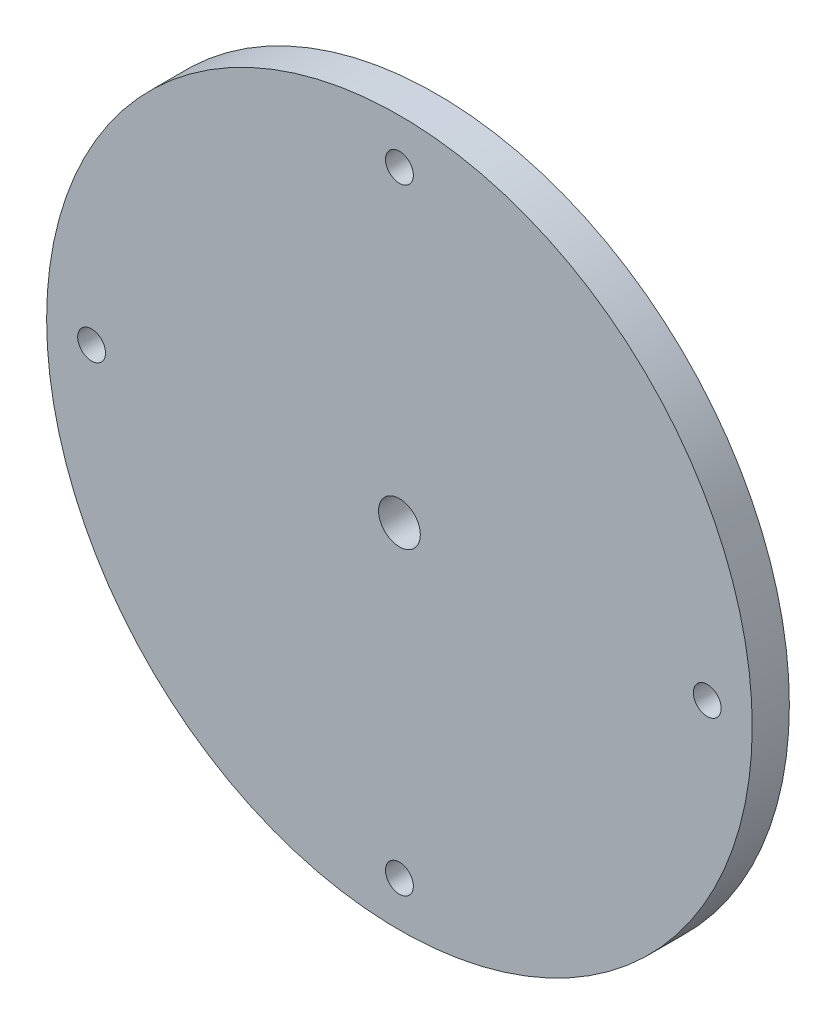
SolidWorks part; units mm, degrees
ref_plane "Front Plane" through (0, 0, 0) normal (0, 0, 1) x (1, 0, 0)
ref_plane "Top Plane" through (0, 0, 0) normal (0, 1, 0) x (1, 0, 0)
ref_plane "Right Plane" through (0, 0, 0) normal (1, 0, 0) x (0, 0, -1)
sketch "Sketch2" plane through (0, 0, 0) normal (0, 0, 1) x (1, 0, 0)
  line L0 (-76, 0) -> (76, 0) construction
  line L2 (0, -76) -> (0, 76) construction
  circle A0 centre (0, 0) radius 76
  circle A1 centre (0, 66.31) radius 3
  circle A2 centre (0, -66.31) radius 3
  circle A3 centre (66.31, 0) radius 3
  circle A4 centre (-66.31, 0) radius 3
  circle A5 centre (0, 0) radius 4.5
  dimension "D1" = 152
  dimension "D6" = 6
  dimension "D7" = 6
  dimension "D8" = 6
  dimension "D9" = 6
  dimension "9.525" = 9
  dimension "D2" = 9.69
  dimension "D3" = 9.69
  dimension "D4" = 9.69
  dimension "D5" = 9.69
extrude "Boss-Extrude1" add sketch "Sketch2" along normal blind 8 contours A0
